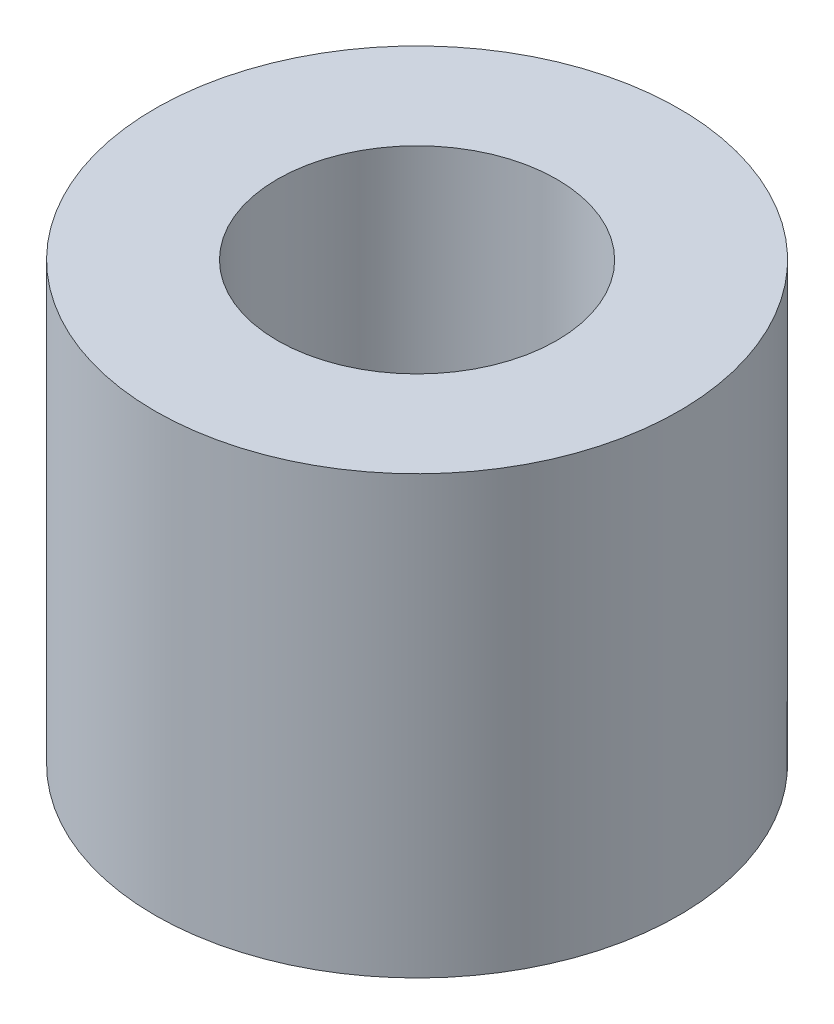
SolidWorks part; units mm, degrees
ref_plane "Front Plane" through (0, 0, 0) normal (0, 0, 1) x (1, 0, 0)
ref_plane "Top Plane" through (0, 0, 0) normal (0, 1, 0) x (1, 0, 0)
ref_plane "Right Plane" through (0, 0, 0) normal (1, 0, 0) x (0, 0, -1)
sketch "Sketch1" plane through (0, 0, 0) normal (0, 1, 0) x (1, 0, 0)
  circle A0 centre (0, 0) radius 3
  circle A1 centre (0, 0) radius 1.6
  dimension "D1" = 3.2
  dimension "D2" = 6
extrude "Boss-Extrude1" add sketch "Sketch1" along normal blind 5
